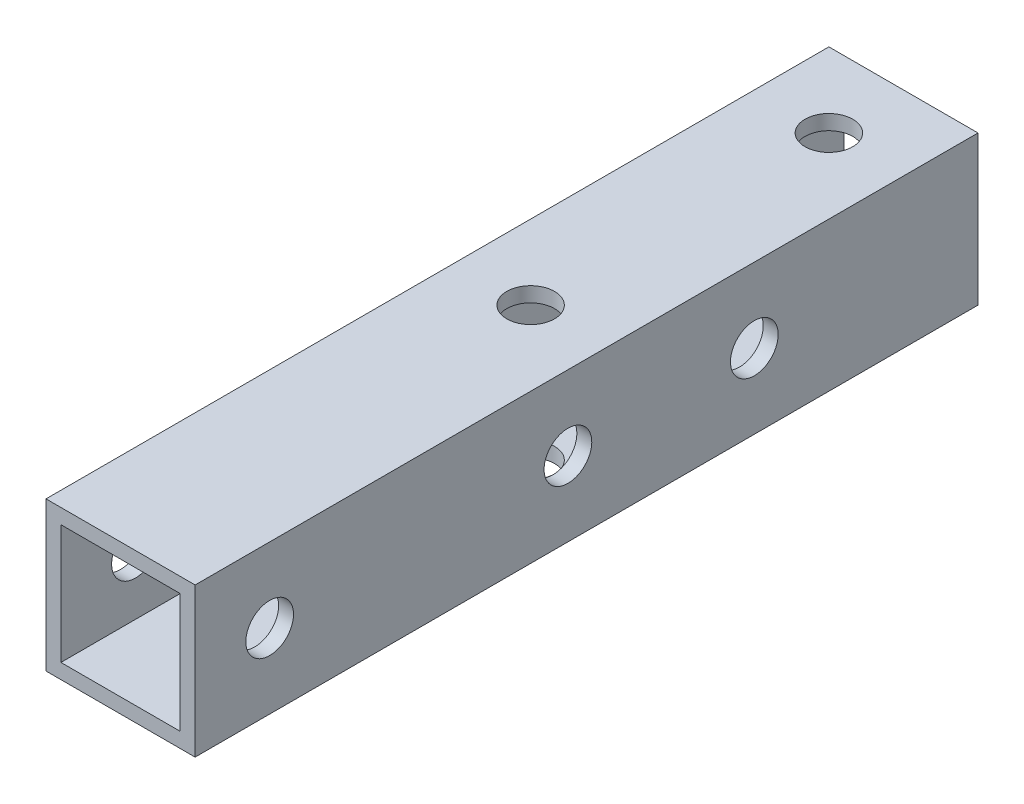
SolidWorks part; units mm, degrees
material "1060 合金"
ref_plane "正面" through (0, 0, 0) normal (0, 0, 1) x (1, 0, 0)
ref_plane "平面" through (0, 0, 0) normal (0, 1, 0) x (1, 0, 0)
ref_plane "右側面" through (0, 0, 0) normal (1, 0, 0) x (0, 0, -1)
sketch "ｽｹｯﾁ1" plane through (0, 0, 0) normal (0, 0, 1) x (1, 0, 0)
  line L1 (5, 5) -> (-5, 5)
  line L2 (5, 5) -> (5, -5)
  line L3 (5, -5) -> (-5, -5)
  line L4 (-5, 5) -> (-5, -5)
  line L5 (5, 5) -> (-5, -5) construction
  line L6 (5, -5) -> (-5, 5) construction
  point P0 (0, 0)
  dimension "D1" = 10
extrude "押し出し-薄板1" add sketch "ｽｹｯﾁ1" along normal blind 52.5 thin thin type one direction reverse wall 1
sketch "ｽｹｯﾁ2" plane through (0, 5, 0) normal (0, 1, 0) x (1, 0, 0)
  line L0 (0, -52.5) -> (0, 0) construction
  line L1 (5, -52.5) -> (-5, -52.5) construction
  line L2 (5, 0) -> (-5, 0) construction
  circle A0 centre (0, -5) radius 1.6
  circle A1 centre (0, -25) radius 1.6
  dimension "D1" = 5
  dimension "D2" = 3.2
  dimension "D3" = 20
  dimension "D4" = 3.2
extrude "ｶｯﾄ - 押し出し1" cut sketch "ｽｹｯﾁ2" against normal through all
sketch "ｽｹｯﾁ3" plane through (5, 0, 0) normal (1, 0, 0) x (0, 0, -1)
  line L0 (-52.5, 0) -> (0, 0) construction
  line L1 (-52.5, -5) -> (-52.5, 5) construction
  circle A0 centre (-47.5, 0) radius 1.6
  circle A2 centre (-27.5, 0) radius 1.6
  dimension "D1" = 3.2
  dimension "D2" = 5
  dimension "D3" = 20
extrude "ｶｯﾄ - 押し出し2" cut sketch "ｽｹｯﾁ3" against normal through all
sketch "ｽｹｯﾁ4" plane through (-5, 0, 0) normal (-1, 0, 0) x (0, 0, 1)
  line L0 (0, 0) -> (52.5, 0) construction
  line L1 (52.5, 5) -> (52.5, -5) construction
  line L2 (0, 5) -> (0, -5) construction
  circle A0 centre (15, 0) radius 1.6
  dimension "D1" = 15
  dimension "D2" = 3.2
extrude "ｶｯﾄ - 押し出し3" cut sketch "ｽｹｯﾁ4" against normal through all
